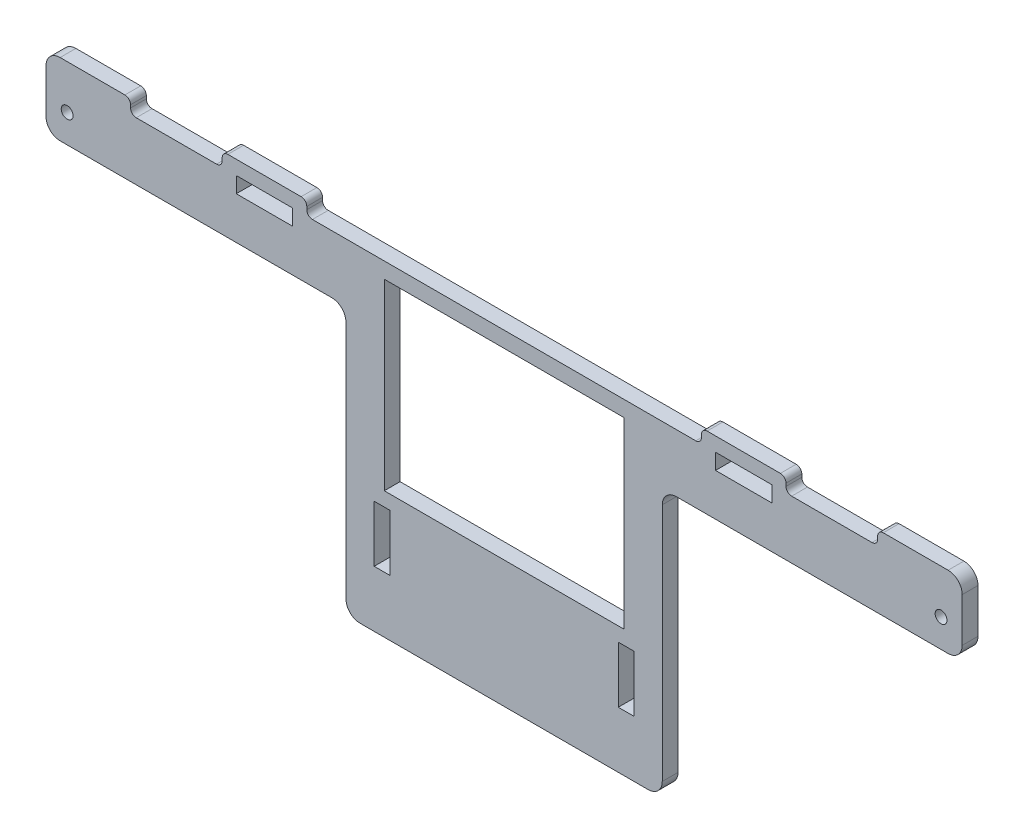
SolidWorks part; units mm, degrees
material "t5ハニカムプラダン"
ref_plane "正面" through (0, 0, 0) normal (0, 0, 1) x (1, 0, 0)
ref_plane "平面" through (0, 0, 0) normal (0, 1, 0) x (1, 0, 0)
ref_plane "右側面" through (0, 0, 0) normal (1, 0, 0) x (0, 0, -1)
sketch "ｽｹｯﾁ1" plane through (0, 0, 0) normal (0, 0, 1) x (1, 0, 0)
  line L0 (0, 0) -> (0, 55) construction
  line L1 (-155, 50) -> (155, 50) construction
  line L2 (-155, 50) -> (-155, -50) construction
  line L3 (-155, -50) -> (155, -50) construction
  line L4 (155, 50) -> (155, -50) construction
  line L5 (-155, 50) -> (155, -50) construction
  line L6 (-155, -50) -> (155, 50) construction
  line L7 (-162.5, 55) -> (162.5, 55)
  line L8 (-162.5, 55) -> (-162.5, -55)
  line L9 (-162.5, -55) -> (162.5, -55)
  line L10 (162.5, 55) -> (162.5, -55)
  line L11 (-162.5, 55) -> (162.5, -55) construction
  line L12 (-162.5, -55) -> (162.5, 55) construction
  line L13 (0, 0) -> (162.5, 0) construction
  circle A0 centre (155, 50) radius 2.1
  circle A1 centre (155, -50) radius 2.1
  circle A2 centre (-155, 50) radius 2.1
  circle A3 centre (-155, -50) radius 2.1
  point P0 (0, 0)
  point P6 (0, 0)
  dimension "D5" = 4.2
  dimension "D1" = 310
  dimension "D2" = 100
  dimension "D3" = 325
  dimension "D4" = 110
extrude "ﾎﾞｽ - 押し出し1" add sketch "ｽｹｯﾁ1" along normal blind 5.6
sketch "ｽｹｯﾁ3" plane through (0, 0, 5.6) normal (0, 0, 1) x (1, 0, 0)
  line L0 (162.5, -55) -> (162.5, 55) construction
  line L1 (-162.5, 55) -> (162.5, 55)
  line L2 (-162.5, 55) -> (-162.5, 65.6)
  line L3 (-162.5, 65.6) -> (162.5, 65.6)
  line L4 (162.5, 55) -> (162.5, 65.6)
  line L5 (0, 0) -> (0, 65.6) construction
  line L6 (75, 55) -> (75, 60.6)
  line L7 (-95, 55) -> (-75, 55)
  line L8 (-95, 55) -> (-95, 60.6)
  line L9 (-95, 60.6) -> (-75, 60.6)
  line L10 (-75, 55) -> (-75, 60.6)
  line L11 (95, 60.6) -> (75, 60.6)
  line L12 (95, 55) -> (95, 60.6)
  line L13 (95, 55) -> (75, 55)
  line M11 (162.5, 55) -> (-162.5, 55)
  dimension "D1" = 10.6
  dimension "D2" = 20
  dimension "D3" = 5.6
  dimension "D4" = 150
extrude "ﾎﾞｽ - 押し出し2" add sketch "ｽｹｯﾁ3" against normal blind 5.6 contours L5 L3 L2 L1 L8 L9 L10 M11 | L5 L1 L6 L11 L12 L4 L3 M11
sketch "ｽｹｯﾁ2" plane through (0, 0, 5.6) normal (0, 0, 1) x (1, 0, 0)
  line L0 (0, 55) -> (0, 22.5) construction
  line L2 (-162.5, -55) -> (162.5, -55) construction
  line L3 (-42.5, -10) -> (42.5, -10)
  line L4 (-42.5, -10) -> (-42.5, 55)
  line L5 (-42.5, 55) -> (42.5, 55)
  line L6 (42.5, -10) -> (42.5, 55)
  line L7 (-42.5, -10) -> (42.5, 55) construction
  line L8 (-42.5, 55) -> (42.5, -10) construction
  line L9 (-46.1, -15) -> (-40.5, -15)
  line L10 (-46.1, -15) -> (-46.1, -35)
  line L11 (-46.1, -35) -> (-40.5, -35)
  line L12 (-40.5, -15) -> (-40.5, -35)
  line L13 (-46.1, -15) -> (-40.5, -35) construction
  line L14 (-46.1, -35) -> (-40.5, -15) construction
  line L15 (46.1, -35) -> (40.5, -15) construction
  line L16 (46.1, -15) -> (40.5, -35) construction
  line L17 (40.5, -15) -> (40.5, -35)
  line L18 (46.1, -35) -> (40.5, -35)
  line L19 (46.1, -15) -> (46.1, -35)
  line L20 (46.1, -15) -> (40.5, -15)
  line L21 (75, 60.6) -> (75, 55)
  line L22 (-95, 60.6) -> (-75, 60.6)
  line L23 (-95, 60.6) -> (-95, 55)
  line L24 (-95, 55) -> (-75, 55)
  line L25 (-75, 60.6) -> (-75, 55)
  line L26 (95, 55) -> (75, 55)
  line L27 (95, 60.6) -> (95, 55)
  line L28 (95, 60.6) -> (75, 60.6)
  point P9 (-43.3, -25)
  point P20 (43.3, -25)
  point P29 (-85, 55)
  dimension "D1" = 85
  dimension "D2" = 65
  dimension "D3" = 20
  dimension "D4" = 5.6
  dimension "D5" = 20
  dimension "D6" = 81
  dimension "D7" = 150
  dimension "D8" = 110
extrude "ｶｯﾄ - 押し出し1" cut sketch "ｽｹｯﾁ2" against normal through all
sketch "ｽｹｯﾁ4" plane through (0, 0, 5.6) normal (0, 0, 1) x (1, 0, 0)
  line L0 (0, 65.6) -> (0, -55) construction
  line L1 (-162.5, -55) -> (-56.1, -55)
  line L2 (-162.5, -55) -> (-162.5, 40)
  line L3 (-162.5, 40) -> (-56.1, 40)
  line L4 (162.5, -55) -> (162.5, 65.6)
  line L5 (162.5, 65.6) -> (-162.5, 65.6)
  line L6 (-162.5, 65.6) -> (-162.5, -55)
  line L7 (-162.5, -55) -> (162.5, -55)
  line L8 (162.5, -55) -> (162.5, 65.6)
  line L9 (162.5, 65.6) -> (-162.5, 65.6)
  line L10 (-162.5, 65.6) -> (-162.5, -55)
  line L11 (-162.5, -55) -> (162.5, -55)
  line L12 (-56.1, -55) -> (-56.1, 40)
  line L13 (56.1, -55) -> (56.1, 40)
  line L14 (162.5, 40) -> (56.1, 40)
  line L15 (162.5, -55) -> (162.5, 40)
  line L16 (162.5, -55) -> (56.1, -55)
  line L17 (-75, 55) -> (-95, 55) construction
  line L18 (-46.1, -15) -> (-46.1, -35) construction
  line M30 (162.5, -55) -> (162.5, 65.6)
  line M32 (-162.5, 65.6) -> (-162.5, -55)
  line M33 (-162.5, -55) -> (162.5, -55)
  circle M34 centre (155, -50) radius 2.1
  circle M35 centre (-155, -50) radius 2.1
  dimension "D2" = 15
  dimension "D3" = 10
  dimension "D1" = 0
extrude "ｶｯﾄ - 押し出し2" cut sketch "ｽｹｯﾁ4" against normal through all contours L12 L3 M33 M32 M35 | L14 L13 L11 M30 M34
sketch "ｽｹｯﾁ5" plane through (0, 0, 5.6) normal (0, 0, 1) x (1, 0, 0)
  line L0 (0, 0) -> (0, 65.6) construction
  line L1 (-162.5, 65.6) -> (162.5, 65.6) construction
  line L2 (-75, 55) -> (-75, 60.6) construction
  line L3 (-70, 60.6) -> (70, 60.6)
  line L4 (-70, 60.6) -> (-70, 65.6)
  line L5 (-70, 65.6) -> (70, 65.6)
  line L6 (70, 60.6) -> (70, 65.6)
  line L7 (-70, 60.6) -> (70, 65.6) construction
  line L8 (-70, 65.6) -> (70, 60.6) construction
  line L9 (-95, 60.6) -> (-75, 60.6) construction
  line L10 (-162.5, 65.6) -> (-162.5, 40) construction
  line L11 (-132.5, 65.6) -> (-100, 65.6)
  line L12 (-132.5, 65.6) -> (-132.5, 60.6)
  line L13 (-132.5, 60.6) -> (-100, 60.6)
  line L14 (-100, 65.6) -> (-100, 60.6)
  line L15 (-95, 55) -> (-95, 60.6) construction
  line L16 (100, 65.6) -> (100, 60.6)
  line L17 (132.5, 60.6) -> (100, 60.6)
  line L18 (132.5, 65.6) -> (132.5, 60.6)
  line L19 (132.5, 65.6) -> (100, 65.6)
  point P5 (0, 63.1)
  dimension "D1" = 5
  dimension "D2" = 30
  dimension "D3" = 5
extrude "ｶｯﾄ - 押し出し3" cut sketch "ｽｹｯﾁ5" against normal through all and the other way through all
fillet "ﾌｨﾚｯﾄ1" radius 5 8 edges at (-162.5, 40, 2.8) (-56.1, 40, 2.8) (-56.1, -55, 2.8) (56.1, -55, 2.8) (56.1, 40, 2.8) (162.5, 40, 2.8) (162.5, 65.6, 2.8) (-162.5, 65.6, 2.8)
fillet "ﾌｨﾚｯﾄ2" radius 2 12 edges at (132.5, 65.6, 2.8) (132.5, 60.6, 2.8) (100, 65.6, 2.8) (100, 60.6, 2.8) (70, 65.6, 2.8) (70, 60.6, 2.8) (-70, 60.6, 2.8) (-70, 65.6, 2.8) (-100, 65.6, 2.8) (-100, 60.6, 2.8) (-132.5, 60.6, 2.8) (-132.5, 65.6, 2.8)
